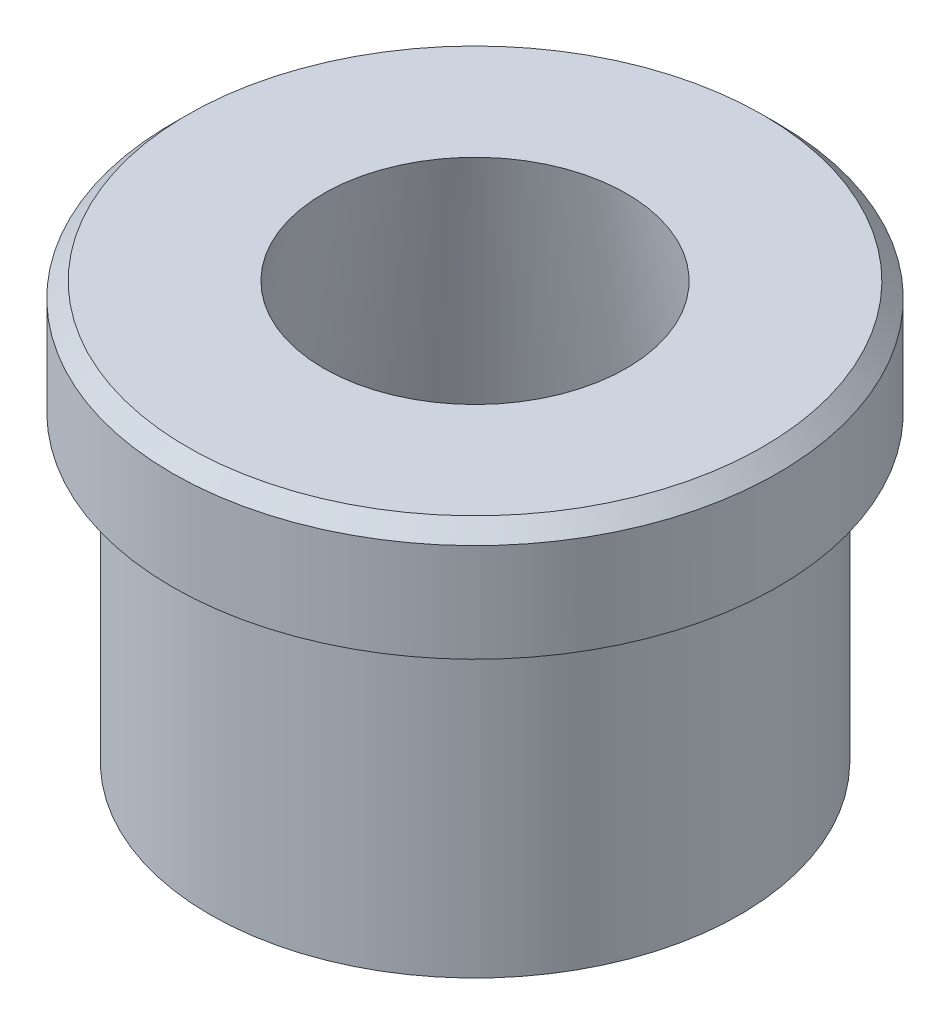
SolidWorks part; units mm, degrees
ref_plane "Front Plane" through (0, 0, 0) normal (0, 0, 1) x (1, 0, 0)
ref_plane "Top Plane" through (0, 0, 0) normal (0, 1, 0) x (1, 0, 0)
ref_plane "Right Plane" through (0, 0, 0) normal (1, 0, 0) x (0, 0, -1)
sketch "Sketch1" plane through (0, 0, 0) normal (0, 0, 1) x (1, 0, 0)
  line L0 (-3, 0) -> (-3.5, 0)
  line L1 (-3.5, 0) -> (-3.5, 4)
  line L2 (-3.5, 4) -> (-4, 4)
  line L3 (-4, 4) -> (-4, 5.5)
  line L4 (-4, 5.5) -> (-2, 5.5)
  line L5 (-2, 5.5) -> (-3, 0)
  line L6 (-2, 5.5) -> (0, 5.5) construction
  line L7 (0, 5.5) -> (0, 0) construction
  line L8 (0, 0) -> (-3, 0) construction
  dimension "D1" = 5.5
  dimension "D2" = 4
  dimension "D3" = 3.5
  dimension "D4" = 1.5
  dimension "D5" = 0.5
  dimension "D6" = 2
revolve "Revolve1" add sketch "Sketch1" angle 360 about L7
chamfer "Chamfer1" distance 0.2 angle 45 2 edges at (0, 0, 3) (0, 5.5, 4)
